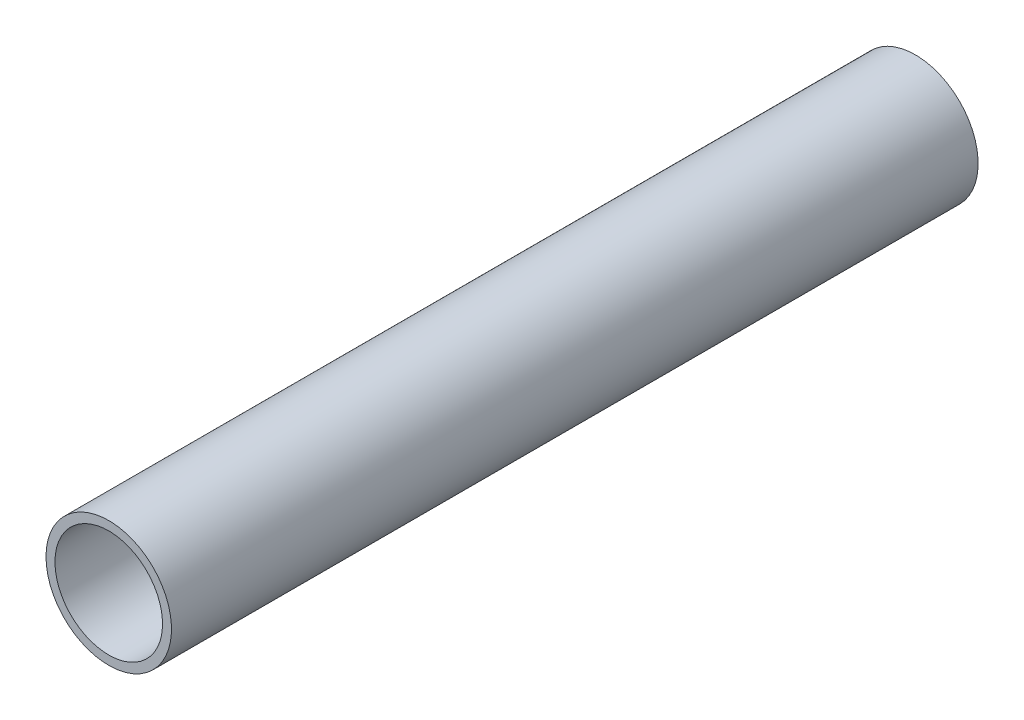
SolidWorks part; units mm, degrees
ref_plane "정면" through (0, 0, 0) normal (0, 0, 1) x (1, 0, 0)
ref_plane "윗면" through (0, 0, 0) normal (0, 1, 0) x (1, 0, 0)
ref_plane "우측면" through (0, 0, 0) normal (1, 0, 0) x (0, 0, -1)
sketch "스케치1" plane through (0, 0, 0) normal (0, 0, 1) x (1, 0, 0)
  circle A0 centre (0, 0) radius 6
  circle A1 centre (0, 0) radius 7
  dimension "D1" = 12
  dimension "D2" = 14
extrude "보스-돌출1" add sketch "스케치1" along normal blind 90
